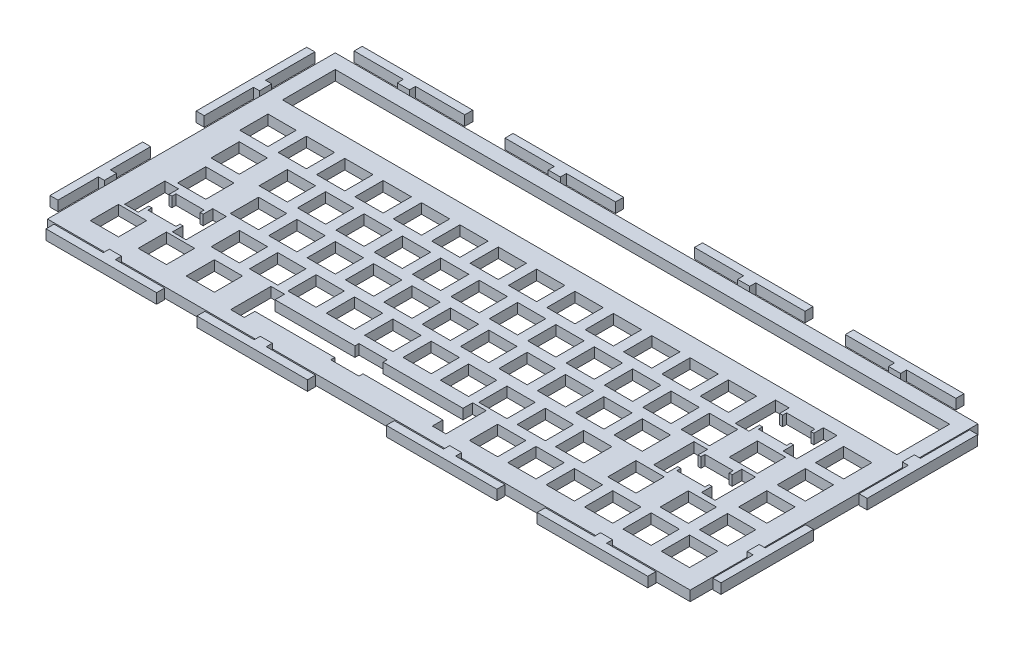
SolidWorks part; units mm, degrees
ref_plane "Front Plane" through (0, 0, 0) normal (0, 0, 1) x (1, 0, 0)
ref_plane "Top Plane" through (0, 0, 0) normal (0, 1, 0) x (1, 0, 0)
ref_plane "Right Plane" through (0, 0, 0) normal (1, 0, 0) x (0, 0, -1)
sketch "Sketch1" plane through (0, 0, 0) normal (0, 1, 0) x (1, 0, 0)
  line L2 (-75.7545, 37.9956) -> (-61.7545, 37.9956)
  line L3 (-94.8265, 37.9956) -> (-80.8265, 37.9956)
  line L4 (-94.8265, 37.9956) -> (-94.8265, 51.9956)
  line L5 (-94.8265, 51.9956) -> (-80.8265, 51.9956)
  line L6 (-80.8265, 37.9956) -> (-80.8265, 51.9956)
  line L7 (-75.7545, 37.9956) -> (-75.7545, 51.9956)
  line L8 (-75.7545, 51.9956) -> (-61.7545, 51.9956)
  line L9 (-61.7545, 37.9956) -> (-61.7545, 51.9956)
  line L10 (133.7495, 37.9956) -> (147.7495, 37.9956)
  line L11 (-37.6545, 37.9956) -> (-23.6545, 37.9956)
  line L12 (-56.7045, 37.9956) -> (-42.7045, 37.9956)
  line L13 (-56.7045, 37.9956) -> (-56.7045, 51.9956)
  line L14 (-56.7045, 51.9956) -> (-42.7045, 51.9956)
  line L15 (-42.7045, 37.9956) -> (-42.7045, 51.9956)
  line L16 (-37.6545, 37.9956) -> (-37.6545, 51.9956)
  line L17 (-37.6545, 51.9956) -> (-23.6545, 51.9956)
  line L18 (-23.6545, 37.9956) -> (-23.6545, 51.9956)
  line L19 (133.7495, 37.9956) -> (133.7495, 51.9956)
  line L20 (133.7495, 51.9956) -> (147.7495, 51.9956)
  line L21 (0.4455, 37.9956) -> (14.4455, 37.9956)
  line L22 (-18.6045, 37.9956) -> (-4.6045, 37.9956)
  line L23 (-18.6045, 37.9956) -> (-18.6045, 51.9956)
  line L24 (-18.6045, 51.9956) -> (-4.6045, 51.9956)
  line L25 (-4.6045, 37.9956) -> (-4.6045, 51.9956)
  line L26 (0.4455, 37.9956) -> (0.4455, 51.9956)
  line L27 (0.4455, 51.9956) -> (14.4455, 51.9956)
  line L28 (14.4455, 37.9956) -> (14.4455, 51.9956)
  line L29 (147.7495, 37.9956) -> (147.7495, 51.9956)
  line L30 (38.5455, 37.9956) -> (52.5455, 37.9956)
  line L31 (19.4955, 37.9956) -> (33.4955, 37.9956)
  line L32 (19.4955, 37.9956) -> (19.4955, 51.9956)
  line L33 (19.4955, 51.9956) -> (33.4955, 51.9956)
  line L34 (33.4955, 37.9956) -> (33.4955, 51.9956)
  line L35 (38.5455, 37.9956) -> (38.5455, 51.9956)
  line L36 (38.5455, 51.9956) -> (52.5455, 51.9956)
  line L37 (52.5455, 37.9956) -> (52.5455, 51.9956)
  line L38 (147.7495, 44.9956) -> (154.1495, 44.9956) construction
  line L39 (167.1835, 18.9456) -> (181.1835, 18.9456)
  line L40 (167.1835, 18.9456) -> (167.1835, 32.9456)
  line L41 (76.6455, 37.9956) -> (90.6455, 37.9956)
  line L42 (57.5955, 37.9956) -> (71.5955, 37.9956)
  line L43 (57.5955, 37.9956) -> (57.5955, 51.9956)
  line L44 (57.5955, 51.9956) -> (71.5955, 51.9956)
  line L45 (71.5955, 37.9956) -> (71.5955, 51.9956)
  line L46 (76.6455, 37.9956) -> (76.6455, 51.9956)
  line L47 (76.6455, 51.9956) -> (90.6455, 51.9956)
  line L48 (90.6455, 37.9956) -> (90.6455, 51.9956)
  line L49 (167.1835, 32.9456) -> (181.1835, 32.9456)
  line L50 (114.7225, 37.9956) -> (128.7225, 37.9956)
  line L51 (95.6955, 37.9956) -> (109.6955, 37.9956)
  line L52 (95.6955, 37.9956) -> (95.6955, 51.9956)
  line L53 (95.6955, 51.9956) -> (109.6955, 51.9956)
  line L54 (109.6955, 37.9956) -> (109.6955, 51.9956)
  line L55 (114.7225, 37.9956) -> (114.7225, 51.9956)
  line L56 (114.7225, 51.9956) -> (128.7225, 51.9956)
  line L57 (128.7225, 37.9956) -> (128.7225, 51.9956)
  line L58 (181.1835, 18.9456) -> (181.1835, 32.9456)
  line L59 (157.3735, 25.9456) -> (167.1835, 25.9456) construction
  line L73 (162.3995, 52.2456) -> (176.3995, 52.2456)
  line L75 (176.3995, 38.2456) -> (162.3995, 38.2456)
  line L77 (176.3995, 52.2456) -> (176.3995, 50.2456)
  line L78 (176.3995, 50.2456) -> (177.8995, 50.2456)
  line L79 (177.8995, 50.2456) -> (177.8995, 54.9956)
  line L80 (177.8995, 54.9956) -> (184.6495, 54.9956)
  line L81 (184.6495, 54.9956) -> (184.6495, 34.9956)
  line L82 (184.6495, 34.9956) -> (177.8995, 34.9956)
  line L83 (177.8995, 34.9956) -> (177.8995, 40.2456)
  line L84 (177.8995, 40.2456) -> (176.3995, 40.2456)
  line L85 (176.3995, 40.2456) -> (176.3995, 38.2456)
  line L86 (162.3995, 52.2456) -> (162.3995, 50.2456)
  line L87 (160.8995, 54.9956) -> (160.8995, 50.2456)
  line L88 (160.8995, 50.2456) -> (162.3995, 50.2456)
  line L89 (160.8995, 54.9956) -> (154.1495, 54.9956)
  line L90 (154.1495, 54.9956) -> (154.1495, 34.9956)
  line L91 (154.1495, 34.9956) -> (160.8995, 34.9956)
  line L92 (160.8995, 34.9956) -> (160.8995, 40.2456)
  line L93 (160.8995, 40.2456) -> (162.3995, 40.2456)
  line L94 (162.3995, 40.2456) -> (162.3995, 38.2456)
  line L116 (-47.1265, 18.9456) -> (-33.1265, 18.9456)
  line L117 (-66.1765, 18.9456) -> (-52.1765, 18.9456)
  line L118 (-66.1765, 18.9456) -> (-66.1765, 32.9456)
  line L119 (-66.1765, 32.9456) -> (-52.1765, 32.9456)
  line L120 (-52.1765, 18.9456) -> (-52.1765, 32.9456)
  line L121 (-47.1265, 18.9456) -> (-47.1265, 32.9456)
  line L122 (-47.1265, 32.9456) -> (-33.1265, 32.9456)
  line L123 (-33.1265, 18.9456) -> (-33.1265, 32.9456)
  line L125 (-9.0515, 18.9456) -> (4.9485, 18.9456)
  line L126 (-28.0765, 18.9456) -> (-14.0765, 18.9456)
  line L127 (-28.0765, 18.9456) -> (-28.0765, 32.9456)
  line L128 (-28.0765, 32.9456) -> (-14.0765, 32.9456)
  line L129 (-14.0765, 18.9456) -> (-14.0765, 32.9456)
  line L130 (-9.0515, 18.9456) -> (-9.0515, 32.9456)
  line L131 (-9.0515, 32.9456) -> (4.9485, 32.9456)
  line L132 (4.9485, 18.9456) -> (4.9485, 32.9456)
  line L135 (29.0735, 18.9456) -> (43.0735, 18.9456)
  line L136 (9.9485, 18.9456) -> (23.9485, 18.9456)
  line L137 (9.9485, 18.9456) -> (9.9485, 32.9456)
  line L138 (9.9485, 32.9456) -> (23.9485, 32.9456)
  line L139 (23.9485, 18.9456) -> (23.9485, 32.9456)
  line L140 (29.0735, 18.9456) -> (29.0735, 32.9456)
  line L141 (29.0735, 32.9456) -> (43.0735, 32.9456)
  line L142 (43.0735, 18.9456) -> (43.0735, 32.9456)
  line L144 (67.1485, 18.9456) -> (81.1485, 18.9456)
  line L145 (48.1235, 18.9456) -> (62.1235, 18.9456)
  line L146 (48.1235, 18.9456) -> (48.1235, 32.9456)
  line L147 (48.1235, 32.9456) -> (62.1235, 32.9456)
  line L148 (62.1235, 18.9456) -> (62.1235, 32.9456)
  line L149 (67.1485, 18.9456) -> (67.1485, 32.9456)
  line L150 (67.1485, 32.9456) -> (81.1485, 32.9456)
  line L151 (81.1485, 18.9456) -> (81.1485, 32.9456)
  line L152 (159.9865, 14.1456) -> (173.9865, 14.1456)
  line L153 (-42.3635, -0.1044) -> (-28.3635, -0.1044)
  line L154 (-61.4135, -0.1044) -> (-47.4135, -0.1044)
  line L155 (105.2735, 18.9456) -> (119.2735, 18.9456)
  line L156 (86.2235, 18.9456) -> (100.2235, 18.9456)
  line L157 (86.2235, 18.9456) -> (86.2235, 32.9456)
  line L158 (86.2235, 32.9456) -> (100.2235, 32.9456)
  line L159 (100.2235, 18.9456) -> (100.2235, 32.9456)
  line L160 (105.2735, 18.9456) -> (105.2735, 32.9456)
  line L161 (105.2735, 32.9456) -> (119.2735, 32.9456)
  line L162 (119.2735, 18.9456) -> (119.2735, 32.9456)
  line L163 (-61.4135, -0.1044) -> (-61.4135, 13.8956)
  line L172 (-94.8265, 37.9956) -> (-94.8265, 32.9456) construction
  line L173 (-61.4135, 13.8956) -> (-47.4135, 13.8956)
  line L174 (-47.4135, -0.1044) -> (-47.4135, 13.8956)
  line L175 (-90.0635, 18.9456) -> (-76.0635, 18.9456)
  line L176 (-90.0635, 18.9456) -> (-90.0635, 32.9456)
  line L177 (-90.0635, 32.9456) -> (-76.0635, 32.9456)
  line L178 (-76.0635, 18.9456) -> (-76.0635, 32.9456)
  line L179 (-94.8265, 32.9456) -> (-90.0635, 32.9456) construction
  line L180 (124.3235, 18.9456) -> (138.3235, 18.9456)
  line L185 (124.3235, 18.9456) -> (124.3235, 32.9456)
  line L186 (124.3235, 32.9456) -> (138.3235, 32.9456)
  line L187 (138.3235, 18.9456) -> (138.3235, 32.9456)
  line L188 (-42.3635, -0.1044) -> (-42.3635, 13.8956)
  line L189 (143.3735, 18.9456) -> (157.3735, 18.9456)
  line L190 (143.3735, 18.9456) -> (143.3735, 32.9456)
  line L191 (143.3735, 32.9456) -> (157.3735, 32.9456)
  line L192 (157.3735, 18.9456) -> (157.3735, 32.9456)
  line L193 (-42.3635, 13.8956) -> (-28.3635, 13.8956)
  line L194 (-28.3635, -0.1044) -> (-28.3635, 13.8956)
  line L195 (-4.2635, -0.1044) -> (9.7365, -0.1044)
  line L196 (-23.3135, -0.1044) -> (-9.3135, -0.1044)
  line L197 (-23.3135, -0.1044) -> (-23.3135, 13.8956)
  line L198 (-23.3135, 13.8956) -> (-9.3135, 13.8956)
  line L199 (-9.3135, -0.1044) -> (-9.3135, 13.8956)
  line L200 (-4.2635, -0.1044) -> (-4.2635, 13.8956)
  line L201 (-4.2635, 13.8956) -> (9.7365, 13.8956)
  line L202 (9.7365, -0.1044) -> (9.7365, 13.8956)
  line L203 (33.8365, -0.1044) -> (47.8365, -0.1044)
  line L204 (14.7865, -0.1044) -> (28.7865, -0.1044)
  line L205 (14.7865, -0.1044) -> (14.7865, 13.8956)
  line L206 (14.7865, 13.8956) -> (28.7865, 13.8956)
  line L207 (28.7865, -0.1044) -> (28.7865, 13.8956)
  line L208 (33.8365, -0.1044) -> (33.8365, 13.8956)
  line L209 (33.8365, 13.8956) -> (47.8365, 13.8956)
  line L210 (47.8365, -0.1044) -> (47.8365, 13.8956)
  line L211 (71.9365, -0.1044) -> (85.9365, -0.1044)
  line L212 (52.8865, -0.1044) -> (66.8865, -0.1044)
  line L213 (52.8865, -0.1044) -> (52.8865, 13.8956)
  line L214 (52.8865, 13.8956) -> (66.8865, 13.8956)
  line L215 (66.8865, -0.1044) -> (66.8865, 13.8956)
  line L216 (71.9365, -0.1044) -> (71.9365, 13.8956)
  line L217 (71.9365, 13.8956) -> (85.9365, 13.8956)
  line L218 (85.9365, -0.1044) -> (85.9365, 13.8956)
  line L219 (110.0365, -0.1044) -> (124.0365, -0.1044)
  line L220 (90.9865, -0.1044) -> (104.9865, -0.1044)
  line L221 (90.9865, -0.1044) -> (90.9865, 13.8956)
  line L222 (90.9865, 13.8956) -> (104.9865, 13.8956)
  line L223 (104.9865, -0.1044) -> (104.9865, 13.8956)
  line L224 (110.0365, -0.1044) -> (110.0365, 13.8956)
  line L225 (110.0365, 13.8956) -> (124.0365, 13.8956)
  line L226 (124.0365, -0.1044) -> (124.0365, 13.8956)
  line L227 (-87.6075, -0.1044) -> (-73.6075, -0.1044)
  line L228 (-87.6075, -0.1044) -> (-87.6075, 13.8956)
  line L229 (-87.6075, 13.8956) -> (-73.6075, 13.8956)
  line L230 (-73.6075, -0.1044) -> (-73.6075, 13.8956)
  line L231 (-90.0635, 18.9456) -> (-90.0635, 13.8956) construction
  line L232 (129.0865, -0.1044) -> (143.0865, -0.1044)
  line L233 (129.0865, -0.1044) -> (129.0865, 13.8956)
  line L234 (129.0865, 13.8956) -> (143.0865, 13.8956)
  line L235 (143.0865, -0.1044) -> (143.0865, 13.8956)
  line L240 (-90.0635, 13.8956) -> (-87.6075, 13.8956) construction
  line L241 (173.9865, 0.1456) -> (159.9865, 0.1456)
  line L242 (173.9865, 14.1456) -> (173.9865, 12.1456)
  line L243 (173.9865, 12.1456) -> (175.4865, 12.1456)
  line L244 (175.4865, 12.1456) -> (175.4865, 16.8956)
  line L245 (175.4865, 16.8956) -> (182.2365, 16.8956)
  line L246 (182.2365, 16.8956) -> (182.2365, -3.1044)
  line L247 (182.2365, -3.1044) -> (175.4865, -3.1044)
  line L248 (175.4865, -3.1044) -> (175.4865, 2.1456)
  line L249 (175.4865, 2.1456) -> (173.9865, 2.1456)
  line L250 (173.9865, 2.1456) -> (173.9865, 0.1456)
  line L251 (159.9865, 14.1456) -> (159.9865, 12.1456)
  line L252 (158.4865, 16.8956) -> (158.4865, 12.1456)
  line L253 (158.4865, 12.1456) -> (159.9865, 12.1456)
  line L254 (158.4865, 16.8956) -> (151.7365, 16.8956)
  line L255 (151.7365, 16.8956) -> (151.7365, -3.1044)
  line L256 (151.7365, -3.1044) -> (158.4865, -3.1044)
  line L257 (158.4865, -3.1044) -> (158.4865, 2.1456)
  line L258 (158.4865, 2.1456) -> (159.9865, 2.1456)
  line L259 (159.9865, 2.1456) -> (159.9865, 0.1456)
  line L260 (143.0865, 12.1456) -> (151.7365, 12.1456) construction
  line L262 (-32.8385, -19.1544) -> (-18.8385, -19.1544)
  line L263 (-51.8885, -19.1544) -> (-37.8885, -19.1544)
  line L264 (-51.8885, -19.1544) -> (-51.8885, -5.1544)
  line L265 (-51.8885, -5.1544) -> (-37.8885, -5.1544)
  line L266 (-37.8885, -19.1544) -> (-37.8885, -5.1544)
  line L267 (-32.8385, -19.1544) -> (-32.8385, -5.1544)
  line L268 (-32.8385, -5.1544) -> (-18.8385, -5.1544)
  line L269 (-18.8385, -19.1544) -> (-18.8385, -5.1544)
  line L270 (5.2615, -19.1544) -> (19.2615, -19.1544)
  line L271 (-13.7885, -19.1544) -> (0.2115, -19.1544)
  line L272 (-13.7885, -19.1544) -> (-13.7885, -5.1544)
  line L273 (-13.7885, -5.1544) -> (0.2115, -5.1544)
  line L274 (0.2115, -19.1544) -> (0.2115, -5.1544)
  line L275 (5.2615, -19.1544) -> (5.2615, -5.1544)
  line L276 (5.2615, -5.1544) -> (19.2615, -5.1544)
  line L277 (19.2615, -19.1544) -> (19.2615, -5.1544)
  line L278 (43.3615, -19.1544) -> (57.3615, -19.1544)
  line L279 (24.3115, -19.1544) -> (38.3115, -19.1544)
  line L280 (24.3115, -19.1544) -> (24.3115, -5.1544)
  line L281 (24.3115, -5.1544) -> (38.3115, -5.1544)
  line L282 (38.3115, -19.1544) -> (38.3115, -5.1544)
  line L283 (43.3615, -19.1544) -> (43.3615, -5.1544)
  line L284 (43.3615, -5.1544) -> (57.3615, -5.1544)
  line L285 (57.3615, -19.1544) -> (57.3615, -5.1544)
  line L286 (81.4615, -19.6544) -> (95.4615, -19.6544)
  line L287 (62.4115, -19.6544) -> (76.4115, -19.6544)
  line L288 (62.4115, -19.6544) -> (62.4115, -5.6544)
  line L289 (62.4115, -5.6544) -> (76.4115, -5.6544)
  line L290 (76.4115, -19.6544) -> (76.4115, -5.6544)
  line L291 (81.4615, -19.6544) -> (81.4615, -5.6544)
  line L292 (81.4615, -5.6544) -> (95.4615, -5.6544)
  line L293 (95.4615, -19.6544) -> (95.4615, -5.6544)
  line L294 (119.5615, -19.6544) -> (133.5615, -19.6544)
  line L295 (100.5115, -19.6544) -> (114.5115, -19.6544)
  line L296 (100.5115, -19.6544) -> (100.5115, -5.6544)
  line L297 (100.5115, -5.6544) -> (114.5115, -5.6544)
  line L298 (114.5115, -19.6544) -> (114.5115, -5.6544)
  line L299 (119.5615, -19.6544) -> (119.5615, -5.6544)
  line L300 (119.5615, -5.6544) -> (133.5615, -5.6544)
  line L301 (133.5615, -19.6544) -> (133.5615, -5.6544)
  line L306 (-83.3445, -5.1544) -> (-69.3445, -5.1544)
  line L307 (145.5235, -19.6544) -> (159.5235, -19.6544)
  line L308 (145.5235, -19.6544) -> (145.5235, -5.6544)
  line L309 (145.5235, -5.6544) -> (159.5235, -5.6544)
  line L310 (159.5235, -19.6544) -> (159.5235, -5.6544)
  line L311 (-69.3445, -19.1544) -> (-83.3445, -19.1544)
  line L331 (171.4855, -19.6544) -> (185.4855, -19.6544)
  line L332 (171.4855, -19.6544) -> (171.4855, -5.6544)
  line L333 (171.4855, -5.6544) -> (185.4855, -5.6544)
  line L334 (185.4855, -19.6544) -> (185.4855, -5.6544)
  line L335 (159.5235, -12.6544) -> (171.4855, -12.6544) construction
  line L336 (-61.4135, -0.1044) -> (-61.4135, -5.1544) construction
  line L337 (-61.4135, -5.1544) -> (-51.8885, -5.1544) construction
  line L338 (-104.4215, 94.9896) -> (-117.5239, 94.9896) construction
  line L339 (-97.2765, 61.6456) -> (207.7235, 61.6456)
  line L340 (190.9955, 18.9456) -> (204.9955, 18.9456)
  line L341 (190.9955, 18.9456) -> (190.9955, 32.9456)
  line L342 (190.9955, 32.9456) -> (204.9955, 32.9456)
  line L343 (204.9955, 18.9456) -> (204.9955, 32.9456)
  line L344 (181.1835, 25.9456) -> (190.9955, 25.9456) construction
  line L345 (190.9745, 37.9956) -> (204.9745, 37.9956)
  line L346 (190.9745, 37.9956) -> (190.9745, 51.9956)
  line L347 (190.9745, 51.9956) -> (204.9745, 51.9956)
  line L348 (204.9745, 37.9956) -> (204.9745, 51.9956)
  line L349 (184.6495, 44.9956) -> (190.9745, 44.9956) construction
  line L350 (190.9425, -0.1044) -> (204.9425, -0.1044)
  line L351 (190.9425, -0.1044) -> (190.9425, 13.8956)
  line L352 (190.9425, 13.8956) -> (204.9425, 13.8956)
  line L353 (204.9425, -0.1044) -> (204.9425, 13.8956)
  line L354 (182.2365, 6.8956) -> (190.9425, 6.8956) construction
  line L355 (190.9855, -19.6544) -> (204.9855, -19.6544)
  line L356 (190.9855, -19.6544) -> (190.9855, -5.6544)
  line L357 (190.9855, -5.6544) -> (204.9855, -5.6544)
  line L358 (204.9855, -19.6544) -> (204.9855, -5.6544)
  line L359 (185.4855, -12.6544) -> (190.9855, -12.6544) construction
  line L360 (-69.3445, -5.1544) -> (-69.3445, -7.1544)
  line L361 (-69.3445, -7.1544) -> (-67.8445, -7.1544)
  line L362 (-67.8445, -7.1544) -> (-67.8445, -2.4044)
  line L363 (-67.8445, -2.4044) -> (-61.0945, -2.4044)
  line L364 (-61.0945, -2.4044) -> (-61.0945, -22.4044)
  line L365 (-61.0945, -22.4044) -> (-67.8445, -22.4044)
  line L366 (-67.8445, -22.4044) -> (-67.8445, -17.1544)
  line L367 (-67.8445, -17.1544) -> (-69.3445, -17.1544)
  line L368 (-69.3445, -17.1544) -> (-69.3445, -19.1544)
  line L369 (-83.3445, -5.1544) -> (-83.3445, -7.1544)
  line L370 (-84.8445, -2.4044) -> (-84.8445, -7.1544)
  line L371 (-84.8445, -7.1544) -> (-83.3445, -7.1544)
  line L372 (-84.8445, -2.4044) -> (-91.5945, -2.4044)
  line L373 (-91.5945, -2.4044) -> (-91.5945, -22.4044)
  line L374 (-91.5945, -22.4044) -> (-84.8445, -22.4044)
  line L375 (-84.8445, -22.4044) -> (-84.8445, -17.1544)
  line L376 (-84.8445, -17.1544) -> (-83.3445, -17.1544)
  line L377 (-83.3445, -17.1544) -> (-83.3445, -19.1544)
  line L378 (-93.0945, -37.9544) -> (-79.0945, -37.9544)
  line L379 (-93.0945, -37.9544) -> (-93.0945, -23.9544)
  line L380 (-93.0945, -23.9544) -> (-79.0945, -23.9544)
  line L381 (-79.0945, -37.9544) -> (-79.0945, -23.9544)
  line L382 (-69.2945, -37.9544) -> (-55.2945, -37.9544)
  line L383 (-69.2945, -37.9544) -> (-69.2945, -23.9544)
  line L384 (-69.2945, -23.9544) -> (-55.2945, -23.9544)
  line L385 (-55.2945, -37.9544) -> (-55.2945, -23.9544)
  line L390 (-45.4945, -37.9544) -> (-31.4945, -37.9544)
  line L391 (-45.4945, -37.9544) -> (-45.4945, -23.9544)
  line L392 (-45.4945, -23.9544) -> (-31.4945, -23.9544)
  line L393 (-31.4945, -37.9544) -> (-31.4945, -23.9544)
  line L394 (-55.2945, -23.9544) -> (-45.4945, -23.9544) construction
  line L395 (26.4395, -24.1144) -> (40.4395, -24.1144)
  line L396 (40.4395, -38.1144) -> (26.4395, -38.1144)
  line L397 (40.4395, -24.1144) -> (40.4395, -26.1144)
  line L398 (40.4395, -26.1144) -> (80.1235, -26.1144)
  line L399 (80.1235, -26.1144) -> (80.1235, -21.3644)
  line L400 (80.1235, -21.3644) -> (86.8735, -21.3644)
  line L401 (86.8735, -21.3644) -> (86.8735, -41.3644)
  line L402 (86.8735, -41.3644) -> (80.1235, -41.3644)
  line L403 (80.1235, -41.3644) -> (80.1235, -36.1144)
  line L404 (80.1235, -36.1144) -> (40.4395, -36.1144)
  line L405 (40.4395, -36.1144) -> (40.4395, -38.1144)
  line L406 (26.4395, -24.1144) -> (26.4395, -26.1144)
  line L407 (-13.2445, -21.3644) -> (-13.2445, -26.1144)
  line L408 (-13.2445, -26.1144) -> (26.4395, -26.1144)
  line L409 (-13.2445, -21.3644) -> (-19.9945, -21.3644)
  line L410 (-19.9945, -21.3644) -> (-19.9945, -41.3644)
  line L411 (-19.9945, -41.3644) -> (-13.2445, -41.3644)
  line L412 (-13.2445, -41.3644) -> (-13.2445, -36.1144)
  line L413 (-13.2445, -36.1144) -> (26.4395, -36.1144)
  line L414 (26.4395, -36.1144) -> (26.4395, -38.1144)
  line L415 (95.5435, -38.3644) -> (109.5435, -38.3644)
  line L416 (95.5435, -38.3644) -> (95.5435, -24.3644)
  line L417 (95.5435, -24.3644) -> (109.5435, -24.3644)
  line L418 (109.5435, -38.3644) -> (109.5435, -24.3644)
  line L419 (86.8735, -31.3644) -> (95.5435, -31.3644) construction
  line L420 (114.5935, -38.3644) -> (128.5935, -38.3644)
  line L421 (114.5935, -38.3644) -> (114.5935, -24.3644)
  line L422 (114.5935, -24.3644) -> (128.5935, -24.3644)
  line L423 (128.5935, -38.3644) -> (128.5935, -24.3644)
  line L424 (114.5935, -31.3644) -> (109.5435, -31.3644) construction
  line L425 (133.6435, -38.3644) -> (147.6435, -38.3644)
  line L426 (133.6435, -38.3644) -> (133.6435, -24.3644)
  line L427 (133.6435, -24.3644) -> (147.6435, -24.3644)
  line L428 (147.6435, -38.3644) -> (147.6435, -24.3644)
  line L429 (152.6935, -38.3644) -> (166.6935, -38.3644)
  line L430 (152.6935, -38.3644) -> (152.6935, -24.3644)
  line L431 (152.6935, -24.3644) -> (166.6935, -24.3644)
  line L432 (166.6935, -38.3644) -> (166.6935, -24.3644)
  line L433 (171.7435, -38.3644) -> (185.7435, -38.3644)
  line L434 (171.7435, -38.3644) -> (171.7435, -24.3644)
  line L435 (171.7435, -24.3644) -> (185.7435, -24.3644)
  line L436 (185.7435, -38.3644) -> (185.7435, -24.3644)
  line L437 (190.7935, -38.3644) -> (204.7935, -38.3644)
  line L438 (190.7935, -38.3644) -> (190.7935, -24.3644)
  line L439 (190.7935, -24.3644) -> (204.7935, -24.3644)
  line L440 (204.7935, -38.3644) -> (204.7935, -24.3644)
  line L441 (-97.2765, 61.6456) -> (-97.2765, 87.8456)
  line L442 (-97.2765, 87.8456) -> (207.7235, 87.8456)
  line L443 (207.7235, 61.6456) -> (207.7235, 87.8456)
  line L444 (-104.4215, 94.9896) -> (214.6585, 94.9896)
  line L445 (-104.4215, 94.9896) -> (-104.4215, -47.8854)
  line L446 (-104.4215, -47.8854) -> (214.6585, -47.8854)
  line L447 (214.6585, 94.9896) -> (214.6585, -47.8854)
  line L448 (-117.5239, 94.9896) -> (-117.5239, 25.8096) construction
  line L449 (-104.4215, -47.8854) -> (-117.5239, -47.8854) construction
  line L450 (-117.5239, -47.8854) -> (-117.5239, 14.6046) construction
  line L451 (-150.5498, 25.8096) -> (-98.6233, 25.8096) construction
  line L452 (-150.5498, 14.6046) -> (-97.2765, 14.6046) construction
  line L453 (-104.4215, 94.9896) -> (-104.4215, 60.3996) construction
  point P115 (128.7225, 44.9956)
  point P116 (154.1495, 44.9956)
  point P239 (0, 0)
  dimension "D1" = 14
  dimension "D2" = 20
  dimension "D3" = 4.75
  dimension "D4" = 6.75
  dimension "D5" = 1.5
  dimension "D6" = 2
  dimension "D13" = 14
  dimension "D14" = 14
  dimension "D15" = 5.072
  dimension "D16" = 14
  dimension "D17" = 5.05
  dimension "D18" = 5.05
  dimension "D19" = 14
  dimension "D20" = 4.763
  dimension "D21" = 5.05
  dimension "D22" = 9.887
  dimension "D23" = 26.2
  dimension "D24" = 14
  dimension "D25" = 14
  dimension "D26" = 5.05
  dimension "D27" = 5.05
  dimension "D28" = 5.05
  dimension "D29" = 5.05
  dimension "D30" = 5.05
  dimension "D31" = 5.05
  dimension "D32" = 5.05
  dimension "D33" = 5.05
  dimension "D34" = 5.05
  dimension "D35" = 5.027
  dimension "D36" = 5.05
  dimension "D37" = 5.05
  dimension "D38" = 5.025
  dimension "D39" = 5
  dimension "D40" = 5.125
  dimension "D41" = 5.05
  dimension "D42" = 5.025
  dimension "D43" = 5.075
  dimension "D44" = 5.05
  dimension "D45" = 5.05
  dimension "D46" = 5.027
  dimension "D47" = 14.65
  dimension "D48" = 14
  dimension "D49" = 9.81
  dimension "D50" = 12.194
  dimension "D51" = 5.05
  dimension "D52" = 5.05
  dimension "D53" = 5.05
  dimension "D54" = 5.05
  dimension "D55" = 5.05
  dimension "D56" = 5.05
  dimension "D57" = 5.05
  dimension "D58" = 5.05
  dimension "D59" = 5.05
  dimension "D60" = 5.05
  dimension "D61" = 14
  dimension "D62" = 20
  dimension "D63" = 5.05
  dimension "D64" = 2.456
  dimension "D65" = 4.75
  dimension "D66" = 6.75
  dimension "D67" = 1.5
  dimension "D68" = 2
  dimension "D69" = 16.9
  dimension "D70" = 14
  dimension "D71" = 5.05
  dimension "D72" = 5.05
  dimension "D73" = 5.05
  dimension "D74" = 5.05
  dimension "D75" = 5.05
  dimension "D76" = 5.05
  dimension "D77" = 5.05
  dimension "D78" = 5.05
  dimension "D79" = 5.05
  dimension "D80" = 11.962
  dimension "D81" = 20
  dimension "D82" = 14
  dimension "D83" = 11.962
  dimension "D84" = 14
  dimension "D85" = 14
  dimension "D86" = 9.812
  dimension "D87" = 14
  dimension "D88" = 14.575
  dimension "D89" = 4.75
  dimension "D90" = 14
  dimension "D91" = 6.75
  dimension "D92" = 14
  dimension "D93" = 16.956
  dimension "D94" = 14
  dimension "D95" = 5.5
  dimension "D96" = 5.05
  dimension "D97" = 5.05
  dimension "D98" = 9.525
  dimension "D99" = 1.5
  dimension "D100" = 2
  dimension "D101" = 5.05
  dimension "D102" = 9.206
  dimension "D103" = 5.05
  dimension "D104" = 14
  dimension "D105" = 14
  dimension "D106" = 14
  dimension "D107" = 14
  dimension "D108" = 1.5
  dimension "D109" = 9.8
  dimension "D110" = 5.05
  dimension "D111" = 9.8
  dimension "D112" = 5.05
  dimension "D113" = 5.05
  dimension "D114" = 14
  dimension "D115" = 14
  dimension "D116" = 20
  dimension "D117" = 4.75
  dimension "D118" = 6.75
  dimension "D119" = 39.684
  dimension "D120" = 2
  dimension "D121" = 5.05
  dimension "D122" = 11.5
  dimension "D123" = 14
  dimension "D124" = 8.67
  dimension "D125" = 5.25
  dimension "D126" = 14
  dimension "D127" = 5.05
  dimension "D128" = 14
  dimension "D129" = 14
  dimension "D130" = 14
  dimension "D131" = 14
  dimension "D132" = 5.05
  dimension "D133" = 5.05
  dimension "D134" = 5.05
  dimension "D135" = 5.05
  dimension "D136" = 4.8
  dimension "D137" = 5.25
  dimension "D138" = 5.25
  dimension "D139" = 5.25
  dimension "D140" = 305
  dimension "D141" = 9.65
  dimension "D142" = 142.875
  dimension "D143" = 319.08
  dimension "D144" = 7.144
  dimension "D145" = 7.145
  dimension "D146" = 2.45
  dimension "D147" = 69.18
  dimension "D148" = 62.49
extrude "Boss-Extrude2" add sketch "Sketch1" along normal mid plane 5
sketch "Sketch2" plane through (0, 2.5, 0) normal (0, 1, 0) x (1, 0, 0)
  line L0 (-104.4215, 25.7896) -> (-104.4215, 14.6146) construction
  line L1 (-104.4215, -47.8854) -> (-104.4215, 14.6146) construction
  line L2 (-104.4215, 94.9896) -> (-104.4215, -47.8854) construction
  line L3 (-104.4215, 94.9896) -> (-104.4215, 25.7896) construction
  line L4 (-104.4215, 60.3896) -> (-192.4203, 60.3896) construction
  line L5 (-104.4215, 63.3896) -> (-104.4215, 57.3896)
  line L6 (-104.4215, 63.3896) -> (-107.4215, 63.3896)
  line L7 (-104.4215, 57.3896) -> (-107.4215, 57.3896)
  line L8 (-107.4215, 63.3896) -> (-107.4215, 87.8456)
  line L9 (-107.4215, 57.3896) -> (-107.4215, 32.9456)
  line L10 (-107.4215, 87.8456) -> (-111.4215, 87.8456)
  line L11 (-111.4215, 87.8456) -> (-111.4215, 32.9456)
  line L12 (-111.4215, 32.9456) -> (-107.4215, 32.9456)
  line L13 (207.7235, 87.8456) -> (-97.2765, 87.8456) construction
  line L14 (-107.4215, 20.2021) -> (-104.4215, 20.2021) construction
  line L15 (-76.0635, 32.9456) -> (-90.0635, 32.9456) construction
  line L16 (-107.4215, 31.2421) -> (-107.4215, 9.1621) construction
  line L17 (-104.4215, -13.6354) -> (-104.4215, -19.6354)
  line L18 (-104.4215, -13.6354) -> (-107.4215, -13.6354)
  line L19 (-104.4215, -19.6354) -> (-107.4215, -19.6354)
  line L20 (-107.4215, -13.6354) -> (-107.4215, 6.3646)
  line L21 (-107.4215, 6.3646) -> (-111.4215, 6.3646)
  line L22 (-111.4215, 6.3646) -> (-111.4215, -39.6354)
  line L23 (-111.4215, -39.6354) -> (-107.4215, -39.6354)
  line L24 (-107.4215, -39.6354) -> (-107.4215, -19.6354)
  line L25 (214.6585, 14.5646) -> (214.6585, -47.8854) construction
  line L26 (55.1185, 125.0696) -> (55.1185, -78.0627) construction
  line L27 (221.6585, -39.6354) -> (217.6585, -39.6354)
  line L28 (221.6585, 6.3646) -> (221.6585, -39.6354)
  line L29 (217.6585, 6.3646) -> (221.6585, 6.3646)
  line L30 (217.6585, -13.6354) -> (217.6585, 6.3646)
  line L31 (214.6585, -13.6354) -> (217.6585, -13.6354)
  line L32 (214.6585, -13.6354) -> (214.6585, -19.6354)
  line L33 (214.6585, -19.6354) -> (217.6585, -19.6354)
  line L34 (217.6585, -39.6354) -> (217.6585, -19.6354)
  line L35 (214.6585, 63.3896) -> (217.6585, 63.3896)
  line L36 (217.6585, 63.3896) -> (217.6585, 87.8456)
  line L37 (217.6585, 87.8456) -> (221.6585, 87.8456)
  line L38 (221.6585, 87.8456) -> (221.6585, 32.9456)
  line L39 (221.6585, 32.9456) -> (217.6585, 32.9456)
  line L40 (217.6585, 57.3896) -> (217.6585, 32.9456)
  line L41 (214.6585, 57.3896) -> (217.6585, 57.3896)
  line L42 (214.6585, 63.3896) -> (214.6585, 57.3896)
  line L43 (214.6585, -47.8854) -> (214.6585, 94.9896) construction
  line L44 (214.6585, 94.9896) -> (214.6585, 25.7896) construction
  line L45 (214.6585, 25.7896) -> (214.6585, 14.5646) construction
  line L46 (214.6585, 20.1771) -> (217.6585, 20.1771) construction
  line L47 (217.6585, 31.2421) -> (217.6585, 9.1621) construction
  line L48 (55.1185, 94.9896) -> (55.1185, -47.8854) construction
  line L49 (214.6585, 94.9896) -> (-104.4215, 94.9896) construction
  line L50 (-104.4215, -47.8854) -> (214.6585, -47.8854) construction
  line L51 (55.1185, 23.5034) -> (270.1989, 23.5034) construction
  line L52 (55.1185, 23.5034) -> (-168.679, 23.5034) construction
  line L53 (214.6585, 94.9896) -> (56.9085, 94.9896) construction
  line L54 (-104.4215, 94.9896) -> (45.7235, 94.9896) construction
  line L55 (45.7235, 94.9896) -> (56.9085, 94.9896) construction
  line L56 (51.316, 94.9896) -> (51.316, 98.9896) construction
  line L57 (40.276, 98.9896) -> (62.356, 98.9896) construction
  line L58 (170.2335, 94.9896) -> (176.2335, 94.9896)
  line L59 (176.2335, 94.9896) -> (176.2335, 97.9896)
  line L60 (176.2335, 97.9896) -> (200.6835, 97.9896)
  line L61 (200.6835, 97.9896) -> (200.6835, 101.9896)
  line L62 (200.6835, 101.9896) -> (145.7835, 101.9896)
  line L63 (145.7835, 101.9896) -> (145.7835, 97.9896)
  line L64 (145.7835, 97.9896) -> (170.2335, 97.9896)
  line L65 (170.2335, 97.9896) -> (170.2335, 94.9896)
  line L66 (95.3335, 94.9896) -> (101.3335, 94.9896)
  line L67 (101.3335, 94.9896) -> (101.3335, 97.9896)
  line L68 (101.3335, 97.9896) -> (125.7835, 97.9896)
  line L69 (125.7835, 97.9896) -> (125.7835, 101.9896)
  line L70 (125.7835, 101.9896) -> (70.8835, 101.9896)
  line L71 (70.8835, 101.9896) -> (70.8835, 97.9896)
  line L72 (70.8835, 97.9896) -> (95.3335, 97.9896)
  line L73 (95.3335, 97.9896) -> (95.3335, 94.9896)
  line L74 (125.7835, 99.9896) -> (145.7835, 99.9896) construction
  line L75 (135.7835, 94.9896) -> (135.7835, 104.9896) construction
  line L76 (-43.1515, 97.9896) -> (-67.6015, 97.9896)
  line L77 (-43.1515, 101.9896) -> (-43.1515, 97.9896)
  line L78 (-98.0515, 101.9896) -> (-43.1515, 101.9896)
  line L79 (-98.0515, 97.9896) -> (-98.0515, 101.9896)
  line L80 (-73.6015, 97.9896) -> (-98.0515, 97.9896)
  line L81 (-73.6015, 94.9896) -> (-73.6015, 97.9896)
  line L82 (-67.6015, 94.9896) -> (-73.6015, 94.9896)
  line L83 (-67.6015, 97.9896) -> (-67.6015, 94.9896)
  line L84 (7.2985, 97.9896) -> (7.2985, 94.9896)
  line L85 (31.7485, 97.9896) -> (7.2985, 97.9896)
  line L86 (31.7485, 101.9896) -> (31.7485, 97.9896)
  line L87 (-23.1515, 101.9896) -> (31.7485, 101.9896)
  line L88 (-23.1515, 97.9896) -> (-23.1515, 101.9896)
  line L89 (1.2985, 97.9896) -> (-23.1515, 97.9896)
  line L90 (1.2985, 94.9896) -> (1.2985, 97.9896)
  line L91 (7.2985, 94.9896) -> (1.2985, 94.9896)
  line L92 (145.7835, -50.9827) -> (170.2335, -50.9827)
  line L93 (145.7835, -54.9827) -> (145.7835, -50.9827)
  line L94 (200.6835, -54.9827) -> (145.7835, -54.9827)
  line L95 (200.6835, -50.9827) -> (200.6835, -54.9827)
  line L96 (176.2335, -50.9827) -> (200.6835, -50.9827)
  line L97 (176.2335, -47.9827) -> (176.2335, -50.9827)
  line L98 (170.2335, -47.9827) -> (176.2335, -47.9827)
  line L99 (170.2335, -50.9827) -> (170.2335, -47.9827)
  line L100 (95.3335, -50.9827) -> (95.3335, -47.9827)
  line L101 (70.8835, -50.9827) -> (95.3335, -50.9827)
  line L102 (70.8835, -54.9827) -> (70.8835, -50.9827)
  line L103 (125.7835, -54.9827) -> (70.8835, -54.9827)
  line L104 (125.7835, -50.9827) -> (125.7835, -54.9827)
  line L105 (101.3335, -50.9827) -> (125.7835, -50.9827)
  line L106 (101.3335, -47.9827) -> (101.3335, -50.9827)
  line L107 (95.3335, -47.9827) -> (101.3335, -47.9827)
  line L108 (31.7485, -50.9827) -> (7.2985, -50.9827)
  line L109 (31.7485, -54.9827) -> (31.7485, -50.9827)
  line L110 (-23.1515, -54.9827) -> (31.7485, -54.9827)
  line L111 (-23.1515, -50.9827) -> (-23.1515, -54.9827)
  line L112 (1.2985, -50.9827) -> (-23.1515, -50.9827)
  line L113 (1.2985, -47.9827) -> (1.2985, -50.9827)
  line L114 (7.2985, -47.9827) -> (1.2985, -47.9827)
  line L115 (7.2985, -50.9827) -> (7.2985, -47.9827)
  line L116 (-43.1515, -54.9827) -> (-43.1515, -50.9827)
  line L117 (-98.0515, -54.9827) -> (-43.1515, -54.9827)
  line L118 (-98.0515, -50.9827) -> (-98.0515, -54.9827)
  line L119 (-73.6015, -50.9827) -> (-98.0515, -50.9827)
  line L120 (-73.6015, -47.9827) -> (-73.6015, -50.9827)
  line L121 (-67.6015, -47.9827) -> (-73.6015, -47.9827)
  line L122 (-67.6015, -50.9827) -> (-67.6015, -47.9827)
  line L123 (-43.1515, -50.9827) -> (-67.6015, -50.9827)
  line L124 (214.6585, -47.8854) -> (56.9135, -47.8854) construction
  line L126 (-104.4215, -47.8854) -> (45.7225, -47.8854) construction
  line L127 (45.7225, -47.8854) -> (56.9135, -47.8854) construction
  line L128 (51.318, -47.8854) -> (51.318, -52.8854) construction
  line L129 (40.276, -52.8854) -> (62.356, -52.8854) construction
  point P17 (-104.4215, 60.3896)
  point P21 (-104.4215, 60.3896)
  point P28 (-104.4215, 20.2021)
  point P31 (-104.4215, -16.6354)
  point P34 (-104.4215, -16.6354)
  point P84 (51.316, 98.9896)
  point P103 (145.7835, 99.9896)
  point P106 (135.7835, 99.9896)
  point P107 (135.7835, 99.9896)
  dimension "D1" = 69.2
  dimension "D2" = 62.5
  dimension "D3" = 3
  dimension "D4" = 6
  dimension "D5" = 0
  dimension "D6" = 0
  dimension "D7" = 22.08
  dimension "D8" = 3
  dimension "D9" = 6
  dimension "D10" = 3
  dimension "D11" = 20
  dimension "D12" = 4
  dimension "D13" = 4
  dimension "D14" = 62.45
  dimension "D15" = 69.2
  dimension "D16" = 22.08
  dimension "D17" = 157.75
  dimension "D18" = 150.145
  dimension "D19" = 4
  dimension "D20" = 22.08
  dimension "D21" = 6
  dimension "D22" = 3
  dimension "D23" = 4
  dimension "D24" = 54.9
  dimension "D25" = 6
  dimension "D26" = 3
  dimension "D27" = 4
  dimension "D28" = 54.9
  dimension "D29" = 20
  dimension "D30" = 10
  dimension "D31" = 157.745
  dimension "D32" = 150.144
  dimension "D33" = 5
  dimension "D34" = 22.08
extrude "Boss-Extrude3" add sketch "Sketch2" along normal mid plane 5
